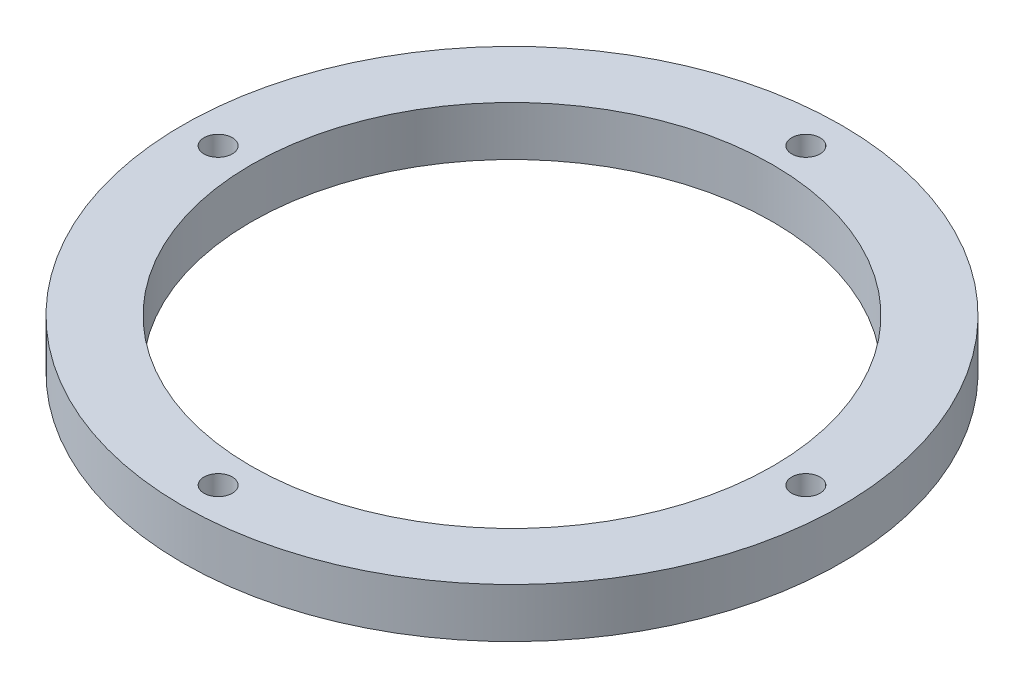
SolidWorks part; units mm, degrees
ref_plane "前视基准面" through (0, 0, 0) normal (0, 0, 1) x (1, 0, 0)
ref_plane "上视基准面" through (0, 0, 0) normal (0, 1, 0) x (1, 0, 0)
ref_plane "右视基准面" through (0, 0, 0) normal (1, 0, 0) x (0, 0, -1)
other "Configuration Table"
sketch "草图1" plane through (0, 0, 0) normal (0, 1, 0) x (1, 0, 0)
  circle A0 centre (0, 0) radius 60
  circle A1 centre (0, 0) radius 47.5
  dimension "D1" = 120
  dimension "D2" = 95
extrude "凸台-拉伸1" add sketch "草图1" along normal blind 9
sketch "草图2" plane through (0, 9, 0) normal (0, 1, 0) x (1, 0, 0)
  line L0 (0, 53.5) -> (0, -0.7655) construction
  circle A0 centre (0, 53.5) radius 2.575
  circle A1 centre (53.5, 0) radius 2.575
  circle A2 centre (0, -53.5) radius 2.575
  circle A3 centre (-53.5, 0) radius 2.575
  point P13 (0, 0)
  dimension "D2" = 5.15
  dimension "D1" = 53.5
  dimension "D3" = 4
extrude "切除-拉伸1" cut sketch "草图2" against normal up to next
